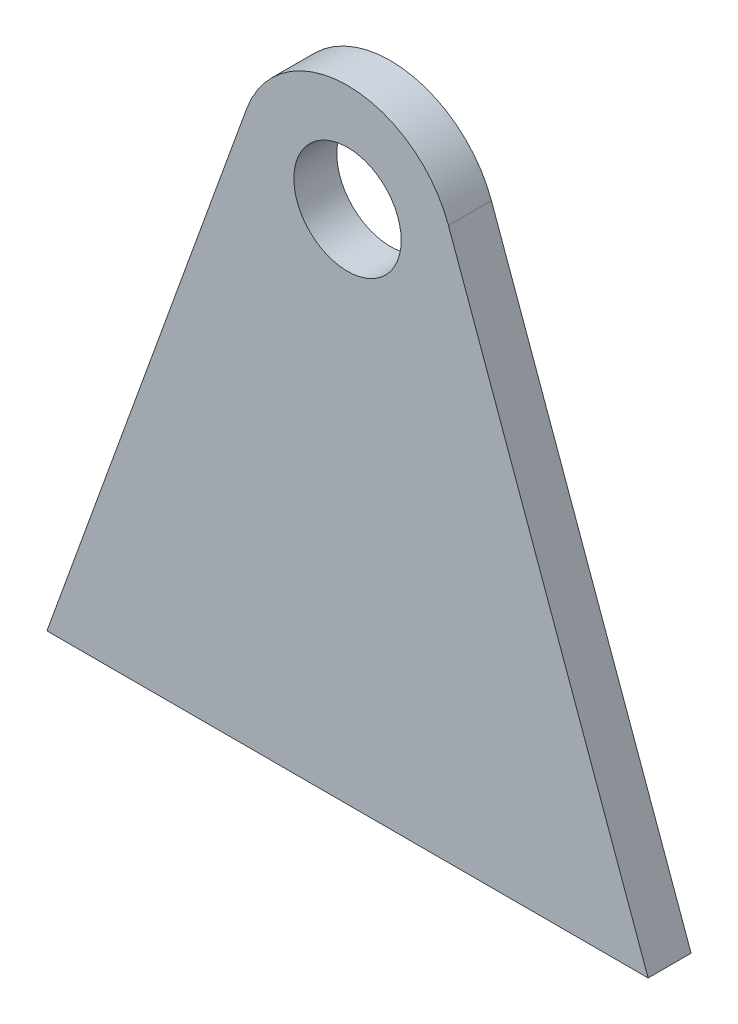
SolidWorks part; units mm, degrees
ref_plane "前基準面" through (0, 0, 0) normal (0, 0, 1) x (1, 0, 0)
ref_plane "上基準面" through (0, 0, 0) normal (0, 1, 0) x (1, 0, 0)
ref_plane "右基準面" through (0, 0, 0) normal (1, 0, 0) x (0, 0, -1)
sketch "草圖1" plane through (0, 0, 0) normal (0, 0, 1) x (1, 0, 0)
  line L0 (0, 0) -> (140, 0)
  line L1 (140, 0) -> (47.0176, 257.0102)
  line L2 (0, 290) -> (0, 0)
  arc A0 (47.0176, 257.0102) -> (0, 290) centre (0, 240) ccw
  dimension "D1" = 50
  dimension "D2" = 290
  dimension "D3" = 140
extrude "填料-伸長1" add sketch "草圖1" along normal blind 20
mirror "鏡射1" about plane through (0, 290, 20) normal (1, 0, 0) of "填料-伸長1"
hole_wizard "Ø20.0mm 定位孔1" positions "草圖2" profile "草圖3" hole size "Ø20.0" standard "ISO" end condition through all
sketch "草圖2" plane through (0, 0, 20) normal (0, 0, 1) x (1, 0, 0)
  point P0 (0, 240)
sketch "草圖3" plane through (0, 240, 20) normal (1, 0, 0) x (0, -1, 0)
  line L0 (0, 0) -> (0, 20)
  line L1 (0, 20) -> (25, 20)
  line L2 (25, 20) -> (25, 0)
  line L5 (25, 0) -> (0, 0)
  line L11 (0, -6.35) -> (0, 107.95) construction
  dimension "貫穿孔直徑" = 50
  dimension "貫穿孔深度" = 20
